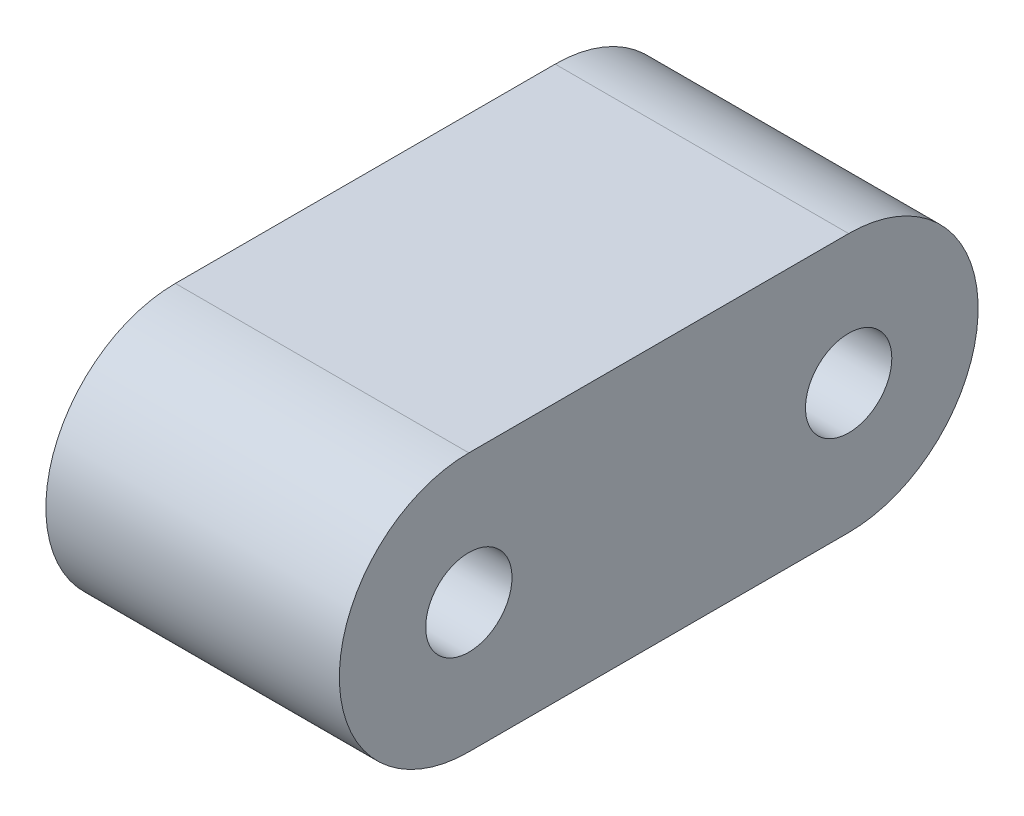
SolidWorks part; units mm, degrees
ref_plane "Alzado" through (0, 0, 0) normal (0, 0, 1) x (1, 0, 0)
ref_plane "Planta" through (0, 0, 0) normal (0, 1, 0) x (1, 0, 0)
ref_plane "Vista lateral" through (0, 0, 0) normal (1, 0, 0) x (0, 0, -1)
sketch "Croquis1" plane through (0, 0, 0) normal (1, 0, 0) x (0, 0, -1)
  line L0 (-11, 0) -> (11, 0) construction
  line L1 (-11, 7.5) -> (11, 7.5)
  line L2 (-11, -7.5) -> (11, -7.5)
  circle A0 centre (-11, 0) radius 2.5
  circle A1 centre (11, 0) radius 2.5
  arc A2 (-11, 7.5) -> (-11, -7.5) centre (-11, 0) ccw
  arc A3 (11, -7.5) -> (11, 7.5) centre (11, 0) ccw
  point P3 (0, 0)
  dimension "D1" = 5
  dimension "D3" = 15
  dimension "D2" = 22
extrude "Saliente-Extruir1" add sketch "Croquis1" along normal mid plane 17
